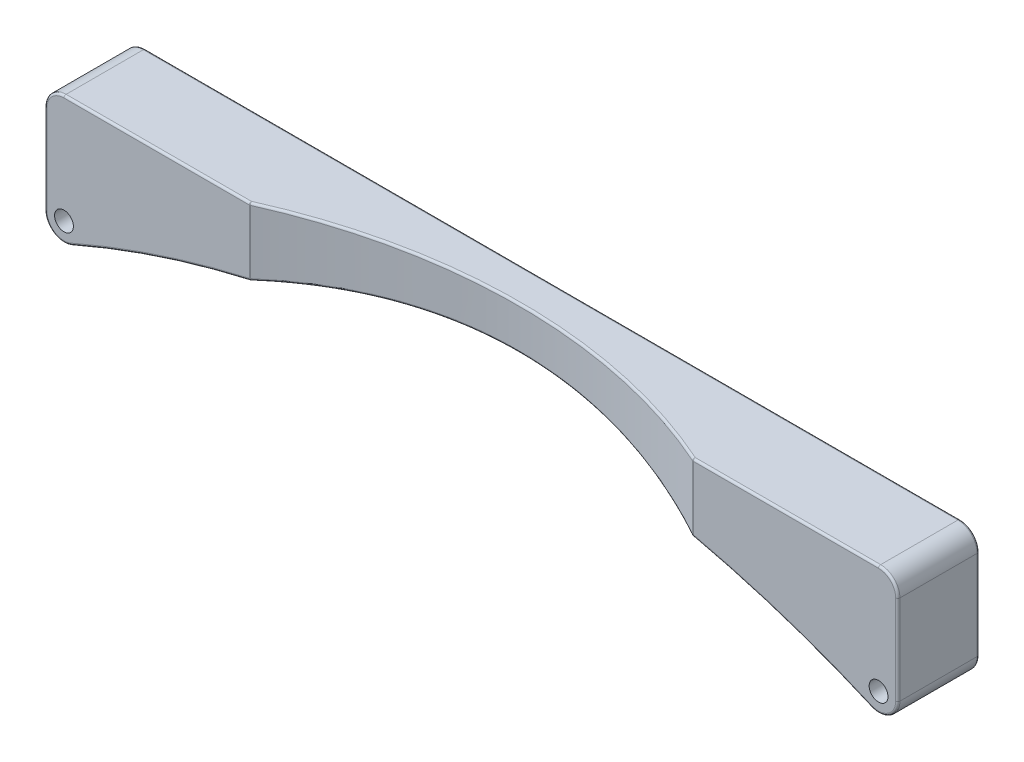
SolidWorks part; units mm, degrees
ref_plane "Front Plane" through (0, 0, 0) normal (0, 0, 1) x (1, 0, 0)
ref_plane "Top Plane" through (0, 0, 0) normal (0, 1, 0) x (1, 0, 0)
ref_plane "Right Plane" through (0, 0, 0) normal (1, 0, 0) x (0, 0, -1)
sketch "Sketch1" plane through (0, 0, 0) normal (0, 0, 1) x (1, 0, 0)
  line L0 (0, 25.4) -> (190.5, 25.4)
  line L1 (-4.5, 0) -> (-4.5, 20.9)
  line L2 (195, 0) -> (195, 20.9)
  circle A0 centre (0, 0) radius 2.2
  circle A1 centre (190.5, 0) radius 2.2
  circle A2 centre (0, 0) radius 4.5
  circle A3 centre (190.5, 0) radius 4.5
  circle A4 centre (0, 20.9) radius 4.5
  circle A5 centre (190.5, 20.9) radius 4.5
  circle A7 centre (95.25, -218.0038) radius 233.4038
  point P20 (95.25, 25.4)
  point P21 (95.25, 15.4)
  dimension "D1" = 4.4
  dimension "D4" = 9
  dimension "D2" = 190.5
  dimension "D3" = 25.4
  dimension "D5" = 10
extrude "Boss-Extrude1" add sketch "Sketch1" along normal blind 19.05 contours A7 A3 L2 A5 L0 A4 L1 A2 | A2 A0 | A4 | A5 | A3 A1
sketch "Sketch2" plane through (0, 25.4, 0) normal (0, 1, 0) x (1, 0, 0)
  line L1 (0, 0) -> (190.5, 0) construction
  line L2 (0, 0) -> (190.5, 0)
  circle A0 centre (95.25, -135) radius 127
  point P0 (95.25, 0)
  point P6 (95.25, -8)
  line M4 (0, -19.05) -> (190.5, -19.05)
  dimension "D2" = 254
  dimension "D1" = 8
extrude "Cut-Extrude1" cut sketch "Sketch2" against normal up to next contours A0 M4
fillet "Fillet1" radius 0.5 22 edges at (192.964, -3.7655, 19.05) (-2.464, -3.7655, 0) (-4.5, 10.45, 0) (-3.182, 24.082, 0) (95.25, 25.4, 0) (193.682, 24.082, 0) (195, 10.45, 0) (192.964, -3.7655, 0) (95.25, 15.4, 0) (195, 10.45, 19.05) (193.682, 24.082, 19.05) (21.7184, 25.4, 19.05) (-3.182, 24.082, 19.05) (22.297, 3.7059, 19.05) (168.7816, 25.4, 19.05) (-4.5, 10.45, 19.05) (147.0631, 17.4882, 19.05) (110.2171, 14.9196, 8.885) (43.4369, 17.4882, 19.05) (95.25, 25.4, 8) (-2.464, -3.7655, 19.05) (168.203, 3.7059, 19.05)
